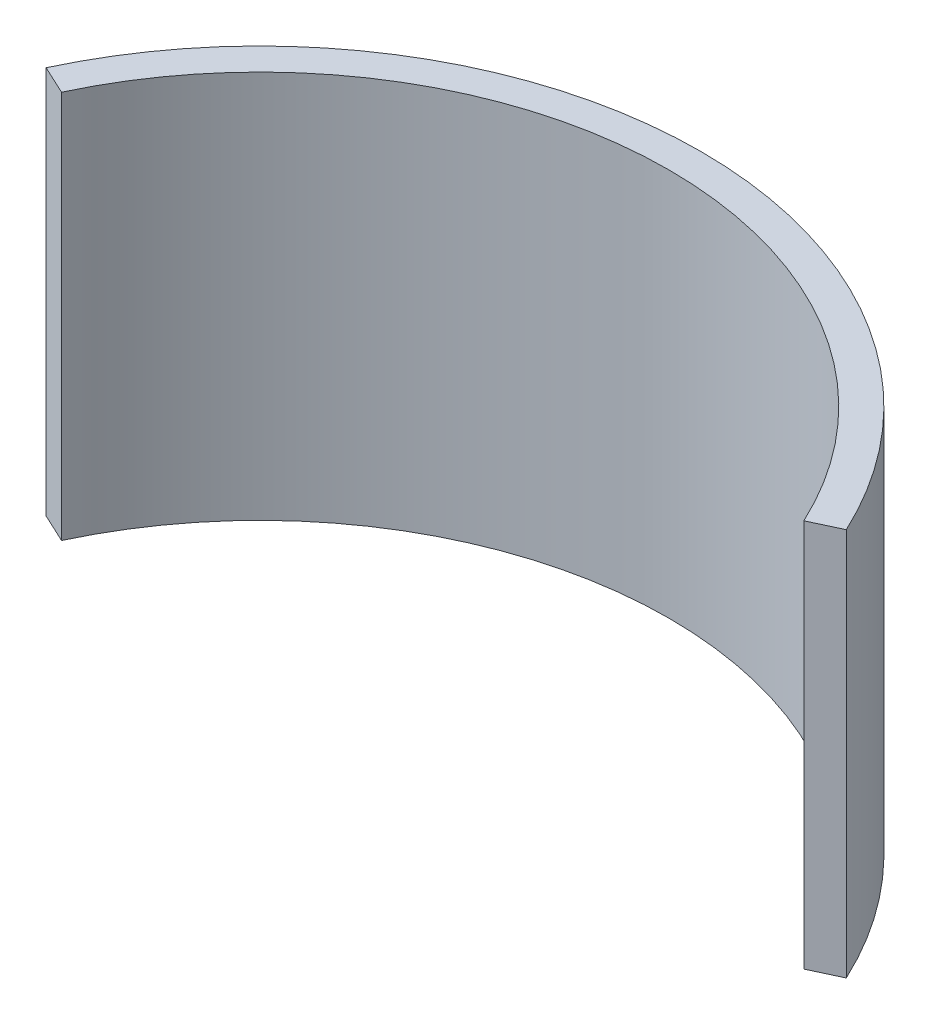
SolidWorks part; units mm, degrees
ref_plane "Front Plane" through (0, 0, 0) normal (0, 0, 1) x (1, 0, 0)
ref_plane "Top Plane" through (0, 0, 0) normal (0, 1, 0) x (1, 0, 0)
ref_plane "Right Plane" through (0, 0, 0) normal (1, 0, 0) x (0, 0, -1)
sketch "Sketch2" plane through (0, 0, 0) normal (1, 0, 0) x (0, 0, -1)
  line L0 (-40, 51.0988) -> (-40, -18.25) construction
  line L1 (-1.5, 18.25) -> (1.5, 18.25)
  line L2 (-1.5, 18.25) -> (-1.5, -18.25)
  line L3 (-1.5, -18.25) -> (1.5, -18.25)
  line L4 (1.5, 18.25) -> (1.5, -18.25)
  line L5 (-1.5, 18.25) -> (1.5, -18.25) construction
  line L6 (-1.5, -18.25) -> (1.5, 18.25) construction
  point P0 (0, 0)
  dimension "D1" = 36.5
  dimension "D2" = 3
  dimension "D3" = 40
revolve "Revolve1" add sketch "Sketch2" angle 65 about L0
